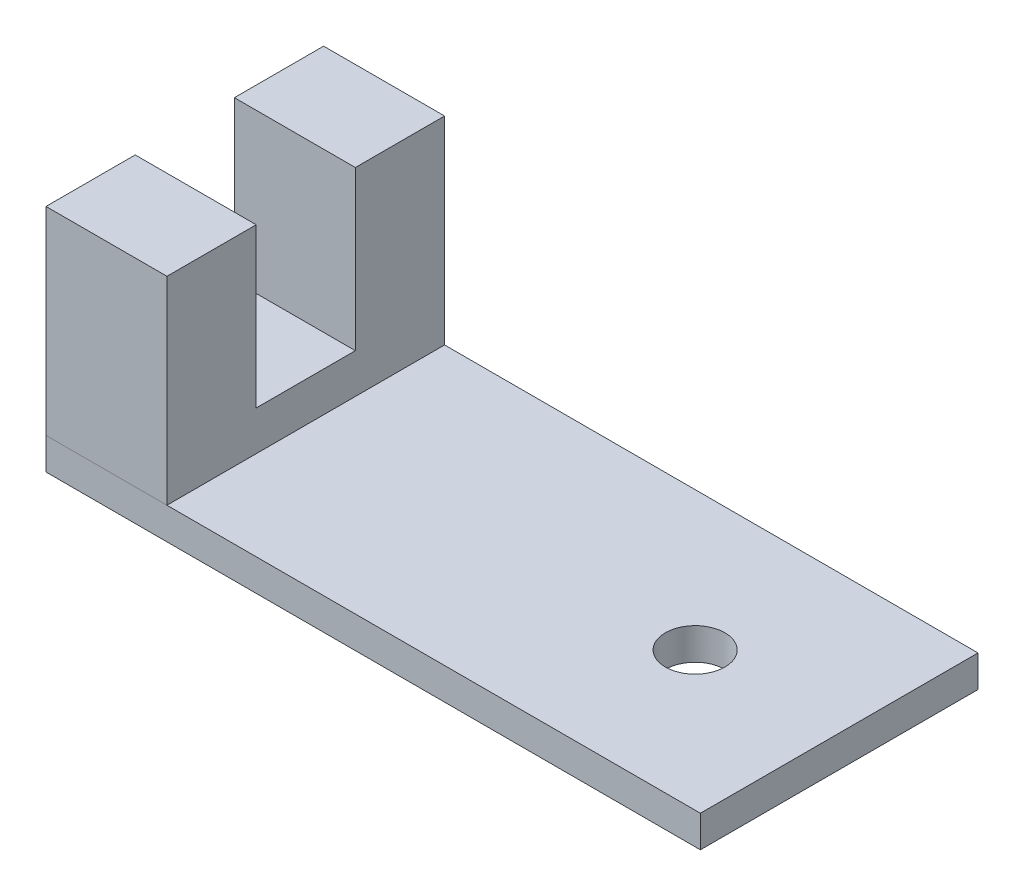
SolidWorks part; units mm, degrees
ref_plane "Front Plane" through (0, 0, 0) normal (0, 0, 1) x (1, 0, 0)
ref_plane "Top Plane" through (0, 0, 0) normal (0, 1, 0) x (1, 0, 0)
ref_plane "Right Plane" through (0, 0, 0) normal (1, 0, 0) x (0, 0, -1)
sketch "Sketch1" plane through (0, 0, 0) normal (0, 1, 0) x (1, 0, 0)
  line L1 (-16.5, -7) -> (16.5, -7)
  line L2 (-16.5, -7) -> (-16.5, 7)
  line L3 (-16.5, 7) -> (16.5, 7)
  line L4 (16.5, -7) -> (16.5, 7)
  line L5 (-16.5, -7) -> (16.5, 7) construction
  line L6 (-16.5, 7) -> (16.5, -7) construction
  point P0 (0, 0)
  dimension "D1" = 33
  dimension "D2" = 14
extrude "Boss-Extrude1" add sketch "Sketch1" along normal blind 1.6
sketch "Sketch2" plane through (-16.5, 0, 0) normal (-1, 0, 0) x (0, 0, 1)
  line L0 (-7, 1.6) -> (-7, 11.6)
  line L1 (-7, 11.6) -> (-2.5, 11.6)
  line L2 (-2.5, 11.6) -> (-2.5, 3.6)
  line L3 (-2.5, 3.6) -> (2.5, 3.6)
  line L4 (2.5, 3.6) -> (2.5, 11.6)
  line L5 (2.5, 11.6) -> (7, 11.6)
  line L6 (7, 11.6) -> (7, 1.6)
  line L7 (-7, 1.6) -> (7, 1.6) construction
  line L8 (7, 1.6) -> (-7, 1.6)
extrude "Boss-Extrude2" add sketch "Sketch2" against normal blind 6.1 separate body
sketch "Sketch3" plane through (-16.5, 0, 0) normal (-1, 0, 0) x (0, 0, 1)
  line L1 (-2.5, 3.6) -> (-2.5, 11.6) construction
  line L2 (-2.5, 9.1) -> (2.5, 9.1)
  line L3 (2.5, 11.6) -> (2.5, 3.6) construction
sketch "Sketch4" plane through (0, 1.6, 0) normal (0, 1, 0) x (1, 0, 0)
  line L0 (16.5, 0) -> (9.235, 0) construction
  line L1 (16.5, -7) -> (16.5, 7) construction
  circle A0 centre (9.235, 0) radius 1.5
extrude "Cut-Extrude1" cut sketch "Sketch4" against normal blind 6.1
